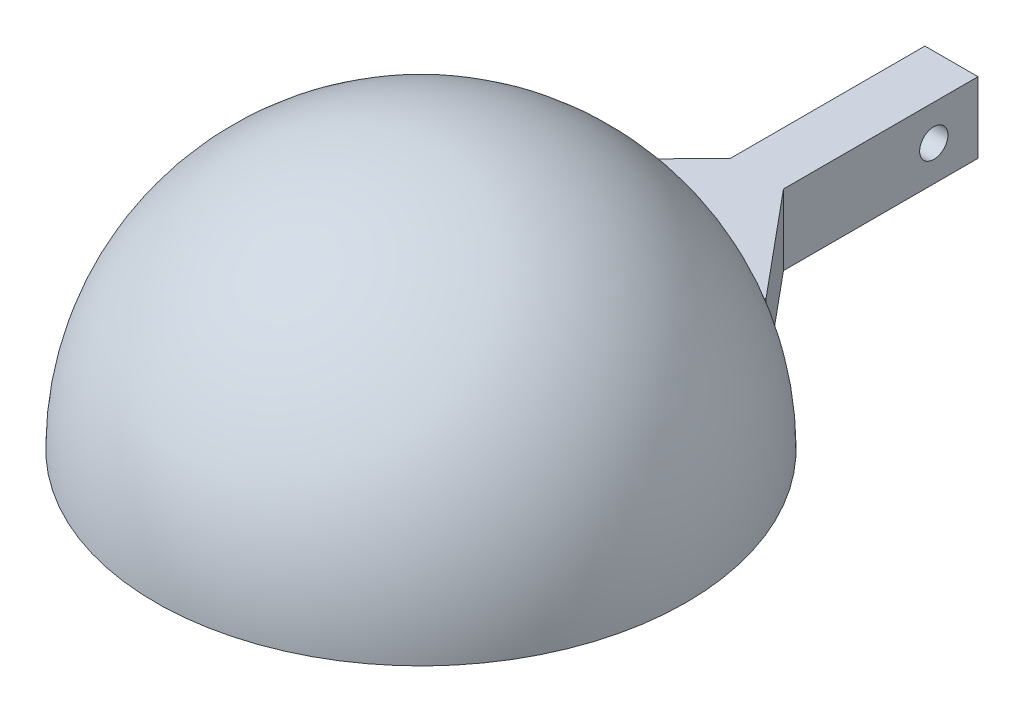
SolidWorks part; units mm, degrees
ref_plane "Front Plane" through (0, 0, 0) normal (0, 0, 1) x (1, 0, 0)
ref_plane "Top Plane" through (0, 0, 0) normal (0, 1, 0) x (1, 0, 0)
ref_plane "Right Plane" through (0, 0, 0) normal (1, 0, 0) x (0, 0, -1)
sketch "Sketch2" plane through (0, 0, 0) normal (0, 0, 1) x (1, 0, 0)
  line L0 (0, 28) -> (0, 30)
  line L1 (28, 0) -> (30, 0)
  line L2 (0, 0) -> (0, 30) construction
  circle A0 centre (0, 0) radius 30 construction
  arc A1 (0, 30) -> (30, 0) centre (0, 0) cw
  arc A2 (0, 28) -> (28, 0) centre (0, 0) cw
  dimension "D1" = 60
  dimension "D2" = 2
revolve "Revolve1" add sketch "Sketch2" angle 360 about L2
sketch "Sketch3" plane through (0, 0, 0) normal (0, -1, 0) x (1, 0, 0)
  line L0 (0, -30) -> (0, -60) construction
  line L1 (-2.539, -38) -> (5.7568, -38) construction
  line L2 (-3, -60) -> (3, -60)
  line L3 (-3, -60) -> (-3, -30)
  line L4 (-3, -30) -> (3, -30)
  line L5 (3, -60) -> (3, -30)
  line L6 (-3, -38) -> (3, -38)
  line L8 (3, -38) -> (12.7228, -26.308)
  line L9 (12.7228, -26.308) -> (12.1903, -25.2071)
  line L10 (-3, -38) -> (-14.4183, -26.308)
  line L11 (-14.4183, -26.308) -> (-13.4571, -24.5541)
  circle A0 centre (0, 0) radius 30 construction
  circle A1 centre (0, 0) radius 30 construction
  circle A2 centre (0, 0) radius 28 construction
  arc A3 (-13.4571, -24.5541) -> (12.1903, -25.2071) centre (0, 0) ccw
  point P9 (0, -60)
  circle M2 centre (0, 0) radius 30
  circle M3 centre (0, 0) radius 28
  dimension "D1" = 30
  dimension "D2" = 8
  dimension "D3" = 6
extrude "Boss-Extrude1" add sketch "Sketch3" against normal blind 8 separate body contours L10 L3 L4 M2 | L3 L6 L5 L4 | L5 L8 L4 M2 | L6 L3 L2 L5 | L11 L9 M2 M3
sketch "Sketch4" plane through (3, 0, 0) normal (1, 0, 0) x (0, 0, -1)
  line L0 (60, 4) -> (41.7869, 4) construction
  line L1 (60, 8) -> (60, 0) construction
  circle A0 centre (55, 4) radius 1.6
  dimension "D1" = 3.2
  dimension "D2" = 5
extrude "Cut-Extrude1" cut sketch "Sketch4" against normal through all
